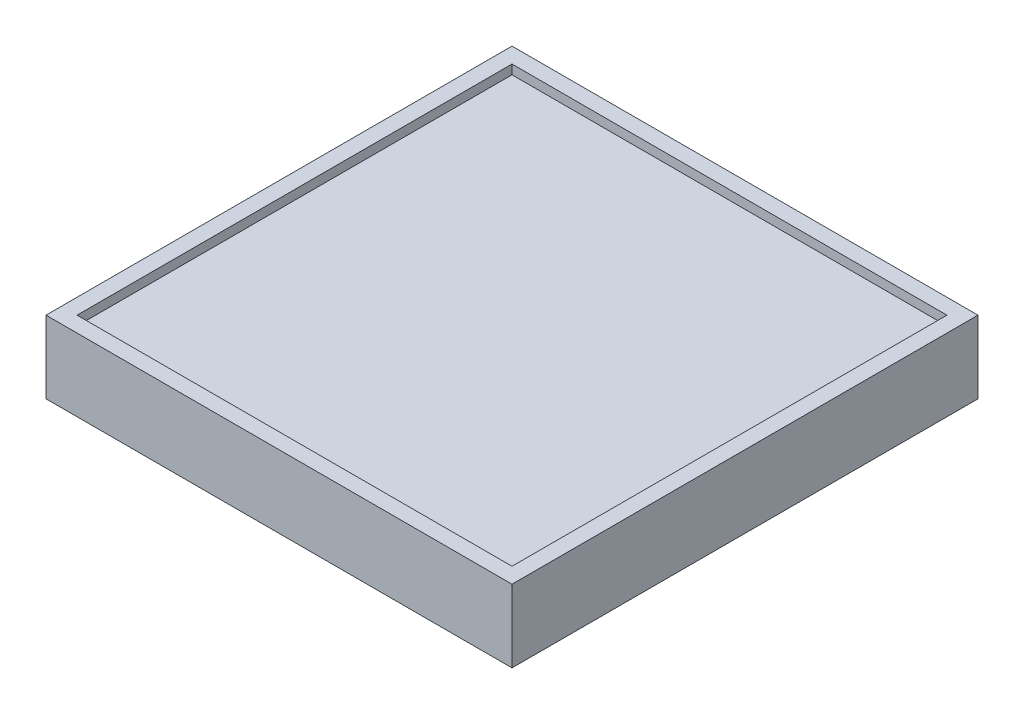
SolidWorks part; units mm, degrees
ref_plane "Front Plane" through (0, 0, 0) normal (0, 0, 1) x (1, 0, 0)
ref_plane "Top Plane" through (0, 0, 0) normal (0, 1, 0) x (1, 0, 0)
ref_plane "Right Plane" through (0, 0, 0) normal (1, 0, 0) x (0, 0, -1)
sketch "Sketch1" plane through (0, 0, 0) normal (0, 1, 0) x (1, 0, 0)
  line L1 (-22.5, 22.5) -> (22.5, 22.5)
  line L2 (-22.5, 22.5) -> (-22.5, -22.5)
  line L3 (-22.5, -22.5) -> (22.5, -22.5)
  line L4 (22.5, 22.5) -> (22.5, -22.5)
  point P4 (-22.5, 0)
  point P7 (0, -22.5)
  dimension "D1" = 45
extrude "Boss-Extrude1" add sketch "Sketch1" along normal blind 7
sketch "Sketch2" plane through (0, 7, 0) normal (0, 1, 0) x (1, 0, 0)
  line L1 (-21, 21) -> (21, 21)
  line L2 (-21, 21) -> (-21, -21)
  line L3 (-21, -21) -> (21, -21)
  line L4 (21, 21) -> (21, -21)
  point P4 (-21, 0)
  point P6 (0, -21)
  dimension "D1" = 42
extrude "Cut-Extrude1" cut sketch "Sketch2" against normal blind 0.9
sketch "Sketch4" plane through (0, 6.1, 0) normal (0, 1, 0) x (1, 0, 0)
  line L1 (-21.75, 21.75) -> (21.75, 21.75)
  line L2 (-21.75, 21.75) -> (-21.75, -21.75)
  line L3 (-21.75, -21.75) -> (21.75, -21.75)
  line L4 (21.75, 21.75) -> (21.75, -21.75)
  point P4 (-21.75, 0)
  point P6 (0, -21.75)
  dimension "D1" = 43.5
extrude "Cut-Extrude2" cut sketch "Sketch4" against normal blind 0.7
